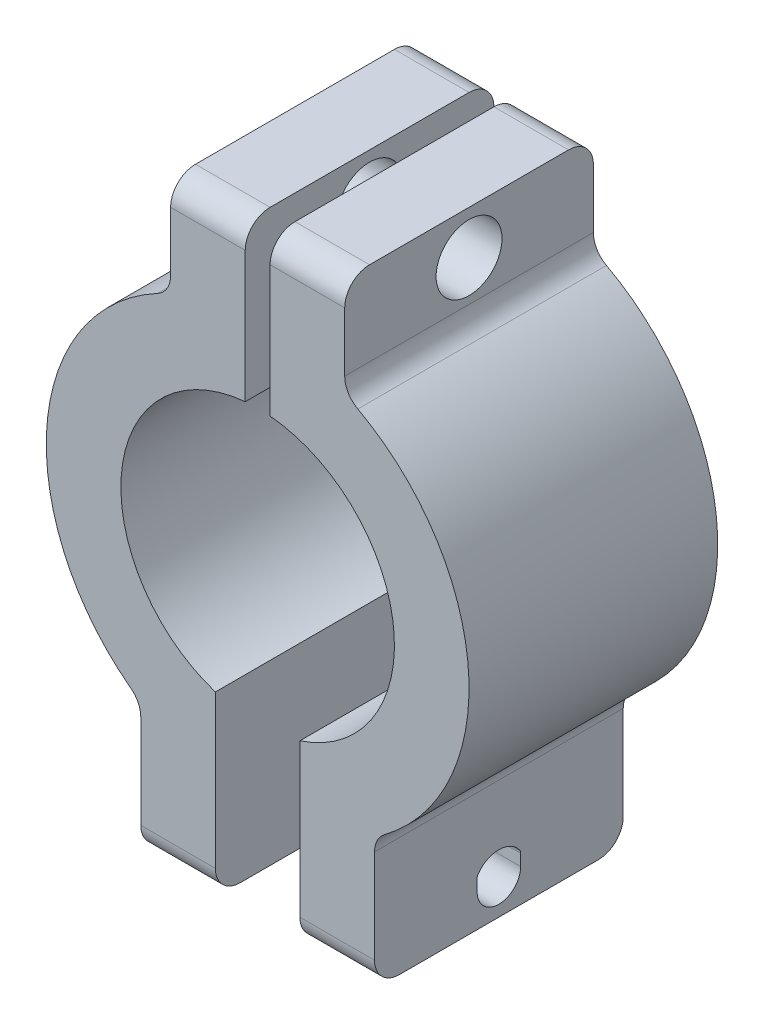
SolidWorks part; units mm, degrees
ref_plane "Front Plane" through (0, 0, 0) normal (0, 0, 1) x (1, 0, 0)
ref_plane "Top Plane" through (0, 0, 0) normal (0, 1, 0) x (1, 0, 0)
ref_plane "Right Plane" through (0, 0, 0) normal (1, 0, 0) x (0, 0, -1)
sketch "Sketch1" plane through (0, 0, 0) normal (0, 0, 1) x (1, 0, 0)
  line L1 (-17, 0) -> (17, 0) construction
  line L2 (-1, 23.4919) -> (-1, 10.9545)
  line L5 (-3.4, -10.4614) -> (-3.4, -24.7493)
  line L6 (-3.4, -24.7493) -> (-9.4, -24.7493)
  line L7 (3.4, -10.4614) -> (3.4, -24.7493)
  line L8 (3.4, -24.7493) -> (9.4, -24.7493)
  line L9 (-9.4, -24.7493) -> (-9.4, -14.1647)
  line L10 (9.4, -24.7493) -> (9.4, -14.1647)
  line L16 (-7, 23.4919) -> (-1, 23.4919)
  line L17 (-7, 15.4919) -> (-7, 23.4919)
  line L18 (7, 15.4919) -> (7, 23.4919)
  line L20 (7, 23.4919) -> (1, 23.4919)
  line L22 (1, 23.4919) -> (1, 10.9545)
  arc A0 (3.4, -10.4614) -> (1, 10.9545) centre (0, 0) ccw
  arc A1 (9.4, -14.1647) -> (7, 15.4919) centre (0, 0) ccw
  arc A2 (-7, 15.4919) -> (-9.4, -14.1647) centre (0, 0) ccw
  arc A3 (-1, 10.9545) -> (-3.4, -10.4614) centre (0, 0) ccw
  point P11 (0, -11)
  point P12 (0, 11)
  point P14 (0, -17)
  point P20 (0, 17)
  dimension "D1" = 22
  dimension "D2" = 8
extrude "Boss-Extrude1" add sketch "Sketch1" along normal blind 20
sketch "Sketch2" plane through (7, 0, 0) normal (1, 0, 0) x (0, 0, -1)
  line L0 (-10, 19.4919) -> (-10, 19.9919) construction
  circle A0 centre (-10, 19.9919) radius 2.65
  dimension "D1" = 5.3
extrude "Cut-Extrude1" cut sketch "Sketch2" against normal blind 14
sketch "Sketch3" plane through (9.4, 0, 0) normal (1, 0, 0) x (0, 0, -1)
  line L0 (-10, -24.7493) -> (-10, -23.8493) construction
  line L1 (-20, -24.7493) -> (0, -24.7493) construction
  line L2 (-10, -20.3493) -> (-10, -20.0493) construction
  line L3 (-11.75, -22.0993) -> (-11.75, -21.1828)
  line L4 (-8.25, -22.0993) -> (-8.25, -21.1828)
  line L5 (-11.75, -22.0993) -> (-8.25, -22.0993) construction
  arc A0 (-11.75, -22.0993) -> (-8.25, -22.0993) centre (-10, -22.0993) ccw
  arc A1 (-8.3468, -20.8871) -> (-11.6532, -20.8871) centre (-10, -22.0993) ccw
  arc A2 (-8.3468, -20.8871) -> (-8.25, -21.1828) centre (-8.75, -21.1828) cw
  arc A3 (-11.75, -21.1828) -> (-11.6532, -20.8871) centre (-11.25, -21.1828) cw
  dimension "D1" = 3.5
  dimension "D2" = 0.5
extrude "Cut-Extrude3" cut sketch "Sketch3" against normal blind 19 contours A1 A3 L3 A0 L4 A2
fillet "Fillet2" radius 2 6 edges at (7, 15.4919, 10) (4, 23.4919, 0) (4, 23.4919, 20) (9.4, -14.1647, 10) (6.4, -24.7493, 20) (6.4, -24.7493, 0)
fillet "Fillet3" radius 2 6 edges at (-6.4, -24.7493, 20) (-6.4, -24.7493, 0) (-9.4, -14.1647, 10) (-7, 15.4919, 10) (-4, 23.4919, 20) (-4, 23.4919, 0)
